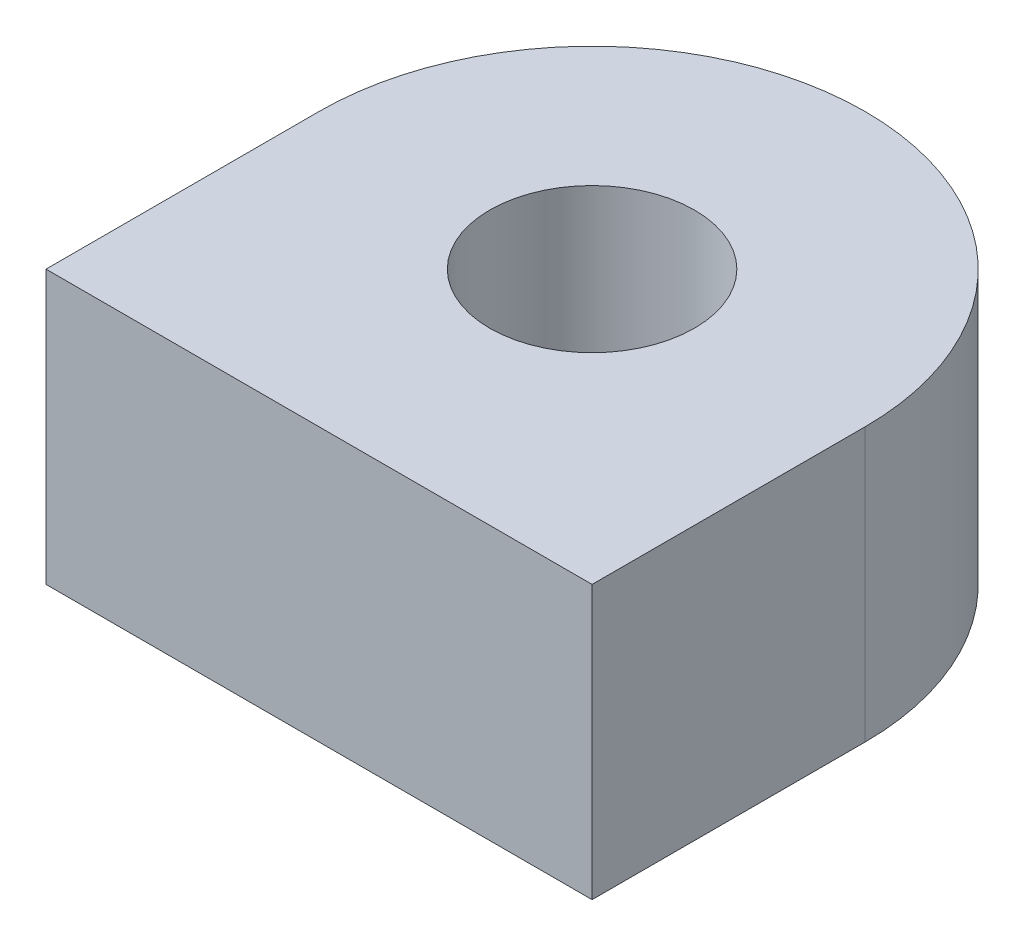
SolidWorks part; units mm, degrees
ref_plane "Front Plane" through (0, 0, 0) normal (0, 0, 1) x (1, 0, 0)
ref_plane "Top Plane" through (0, 0, 0) normal (0, 1, 0) x (1, 0, 0)
ref_plane "Right Plane" through (0, 0, 0) normal (1, 0, 0) x (0, 0, -1)
sketch "Sketch1" plane through (0, 0, 0) normal (0, 1, 0) x (1, 0, 0)
  line L0 (-25.4, 0) -> (-25.4, -25.4)
  line L1 (-25.4, -25.4) -> (25.4, -25.4)
  line L2 (25.4, -25.4) -> (25.4, 0)
  circle A0 centre (0, 0) radius 9.525
  arc A1 (25.4, 0) -> (-25.4, 0) centre (0, 0) ccw
  dimension "D1" = 19.05
  dimension "D2" = 25.4
extrude "Boss-Extrude1" add sketch "Sketch1" along normal blind 25.4
